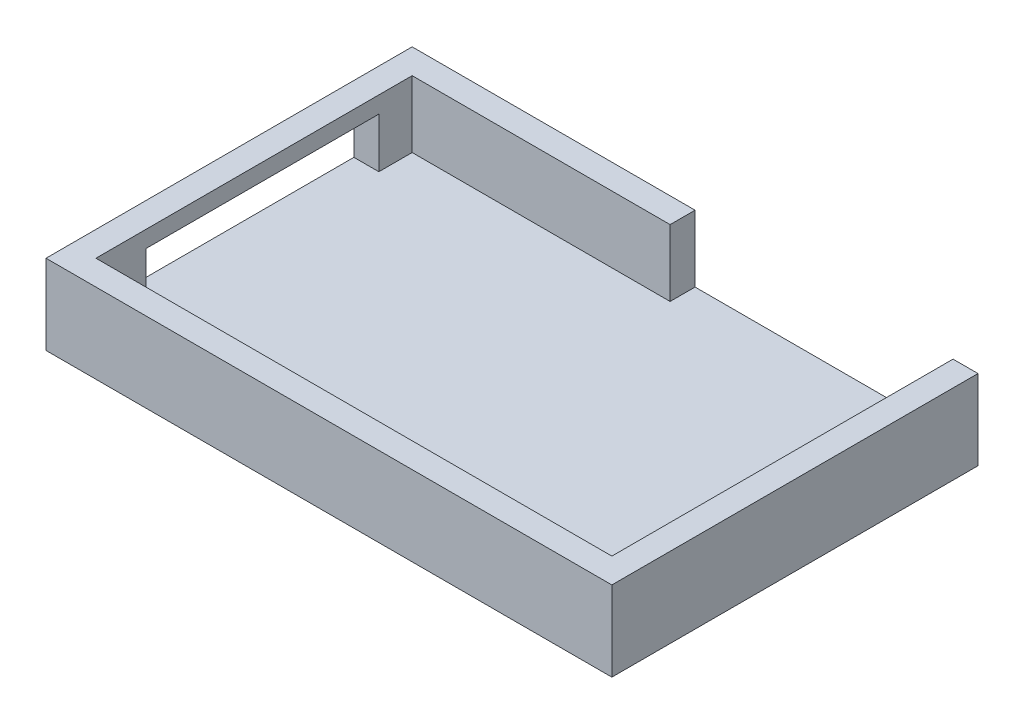
SolidWorks part; units mm, degrees
ref_plane "Alzado" through (0, 0, 0) normal (0, 0, 1) x (1, 0, 0)
ref_plane "Planta" through (0, 0, 0) normal (0, 1, 0) x (1, 0, 0)
ref_plane "Vista lateral" through (0, 0, 0) normal (1, 0, 0) x (0, 0, -1)
sketch "Croquis2" plane through (0, 0, 0) normal (0, 1, 0) x (1, 0, 0)
  line L1 (-85, -55) -> (85, -55)
  line L2 (-85, -55) -> (-85, 55)
  line L3 (-85, 55) -> (85, 55)
  line L4 (85, -55) -> (85, 55)
  line L5 (-85, -55) -> (85, 55) construction
  line L6 (-85, 55) -> (85, -55) construction
  point P0 (0, 0)
extrude "Saliente-Extruir1" add sketch "Croquis2" along normal blind 4
sketch "Croquis3" plane through (0, 4, 0) normal (0, 1, 0) x (1, 0, 0)
  line L1 (77.5, -47.5) -> (-77.5, -47.5)
  line L2 (77.5, -47.5) -> (77.5, 47.5)
  line L3 (77.5, 47.5) -> (-77.5, 47.5)
  line L4 (-77.5, -47.5) -> (-77.5, 47.5)
  line L5 (77.5, -47.5) -> (-77.5, 47.5) construction
  line L6 (77.5, 47.5) -> (-77.5, -47.5) construction
  line L7 (85, -55) -> (-85, -55)
  line L8 (85, -55) -> (85, 55)
  line L9 (85, 55) -> (-85, 55)
  line L10 (-85, -55) -> (-85, 55)
  line L11 (85, -55) -> (-85, 55) construction
  line L12 (85, 55) -> (-85, -55) construction
  point P0 (0, 0)
  point P6 (0, 0)
extrude "Saliente-Extruir2" add sketch "Croquis3" along normal blind 20
sketch "Croquis4" plane through (-77.5, 0, 0) normal (1, 0, 0) x (0, 0, -1)
  line L0 (-47.5, 24) -> (47.5, 4) construction
  line L1 (47.5, 4) -> (-47.5, 4) construction
  line L2 (47.5, 24) -> (-47.5, 4) construction
  line L3 (0, 29.4264) -> (0, -3.3371) construction
  line L8 (37.5, 4) -> (37.5, 19)
  line L14 (-32.5, 4) -> (-32.5, 19)
  line L15 (47.5, 24) -> (47.5, 4) construction
  line L16 (-47.5, 24) -> (-47.5, 4) construction
  line L17 (-32.5, 19) -> (37.5, 19)
  line L19 (-32.5, 4) -> (37.5, 4)
  dimension "D1" = 10
  dimension "D2" = 15
extrude "Cortar-Extruir1" cut sketch "Croquis4" against normal blind 20
sketch "Croquis5" plane through (0, 0, -47.5) normal (0, 0, 1) x (1, 0, 0)
  line L0 (77.5, 24) -> (-77.5, 24) construction
  line L1 (77.5, 4) -> (0, 4)
  line L2 (77.5, 4) -> (77.5, 24)
  line L3 (77.5, 24) -> (0, 24)
  line L4 (0, 4) -> (0, 24)
extrude "Cortar-Extruir2" cut sketch "Croquis5" against normal blind 20
